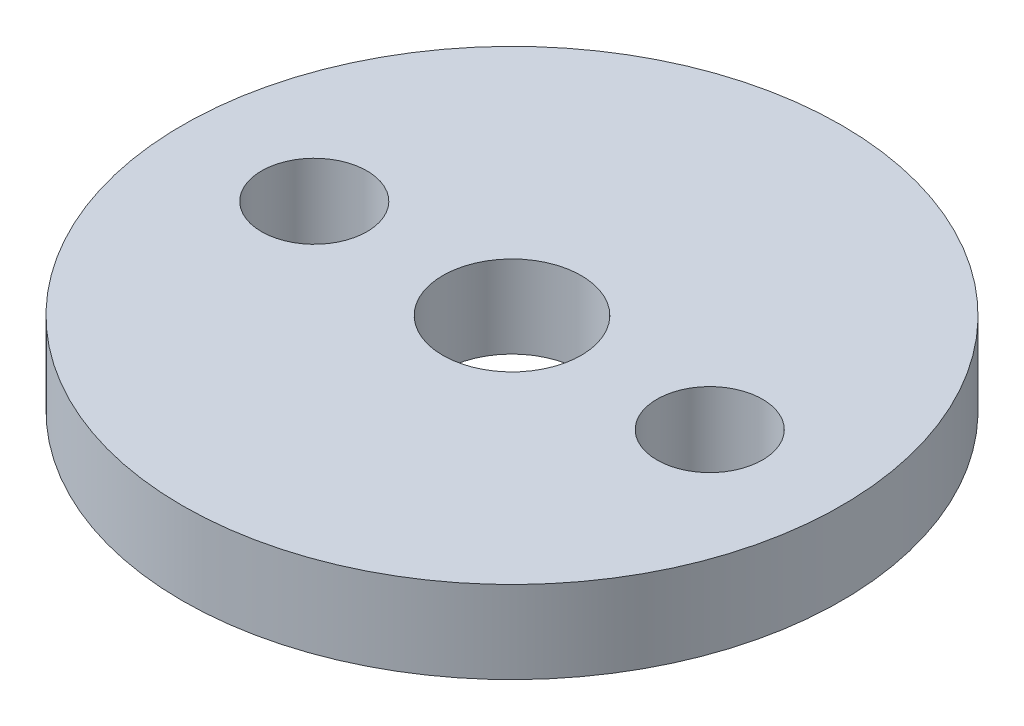
SolidWorks part; units mm, degrees
ref_plane "Front Plane" through (0, 0, 0) normal (0, 0, 1) x (1, 0, 0)
ref_plane "Top Plane" through (0, 0, 0) normal (0, 1, 0) x (1, 0, 0)
ref_plane "Right Plane" through (0, 0, 0) normal (1, 0, 0) x (0, 0, -1)
sketch "Sketch1" plane through (0, 0, 0) normal (0, 1, 0) x (1, 0, 0)
  circle A0 centre (0, 0) radius 10
extrude "Boss-Extrude1" add sketch "Sketch1" along normal blind 2.5
sketch "Sketch2" plane through (0, 0, 0) normal (0, 1, 0) x (1, 0, 0)
  circle A0 centre (0, 0) radius 2.1
  circle A1 centre (6, 0) radius 1.6
  circle A2 centre (-6, 0) radius 1.6
extrude "Cut-Extrude1" cut sketch "Sketch2" against normal through all and the other way through all
